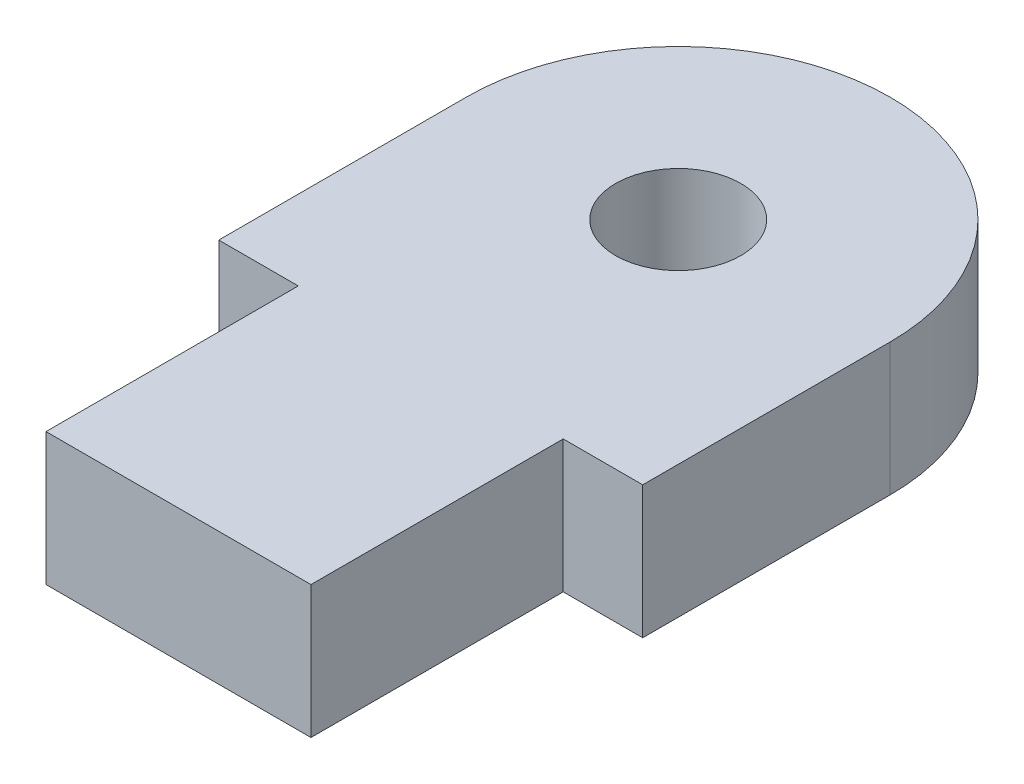
SolidWorks part; units mm, degrees
ref_plane "Front Plane" through (0, 0, 0) normal (0, 0, 1) x (1, 0, 0)
ref_plane "Top Plane" through (0, 0, 0) normal (0, 1, 0) x (1, 0, 0)
ref_plane "Right Plane" through (0, 0, 0) normal (1, 0, 0) x (0, 0, -1)
sketch "Sketch1" plane through (0, 0, 0) normal (0, 1, 0) x (1, 0, 0)
  line L0 (-5.08, 0) -> (-5.08, -5.9309)
  line L1 (-5.08, -5.9309) -> (-3.175, -5.9309)
  line L2 (5.08, -5.9309) -> (5.08, 0)
  line L3 (-3.175, -5.9309) -> (-3.175, -11.9761)
  line L4 (-3.175, -11.9761) -> (3.175, -11.9761)
  line L5 (0, 5.08) -> (0, -11.9761) construction
  line L6 (3.175, -5.9309) -> (3.175, -11.9761)
  line L7 (3.175, -5.9309) -> (5.08, -5.9309)
  circle A0 centre (0, 0) radius 1.5
  arc A1 (5.08, 0) -> (-5.08, 0) centre (0, 0) ccw
  dimension "D1" = 3
  dimension "D2" = 10.16
  dimension "D3" = 5.9309
  dimension "D4" = 6.0452
  dimension "D5" = 3.175
extrude "Boss-Extrude1" add sketch "Sketch1" along normal blind 3.175
